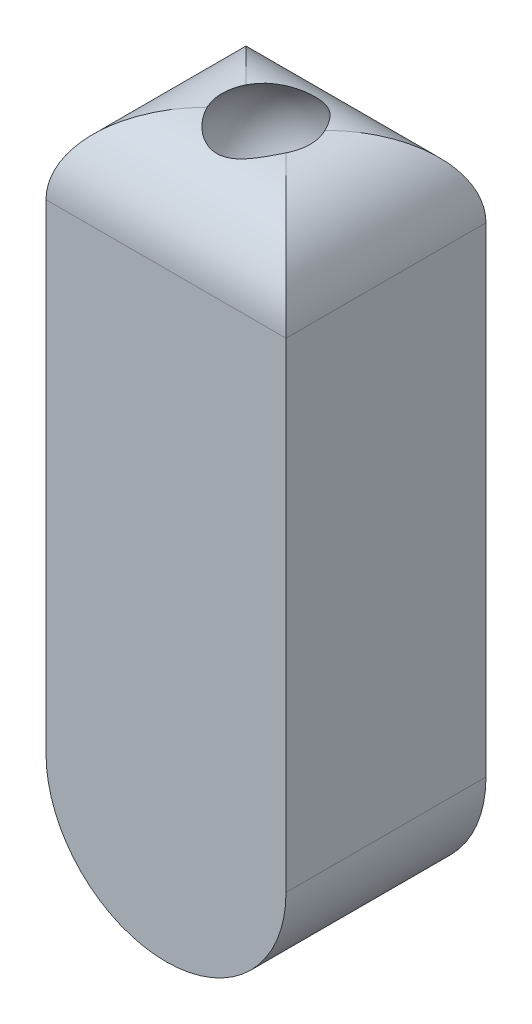
SolidWorks part; units mm, degrees
ref_plane "Front Plane" through (0, 0, 0) normal (0, 0, 1) x (1, 0, 0)
ref_plane "Top Plane" through (0, 0, 0) normal (0, 1, 0) x (1, 0, 0)
ref_plane "Right Plane" through (0, 0, 0) normal (1, 0, 0) x (0, 0, -1)
sketch "Sketch1" plane through (0, 0, 0) normal (0, 0, 1) x (1, 0, 0)
  line L1 (-38.1, 88.9) -> (38.1, 88.9)
  line L2 (-38.1, 88.9) -> (-38.1, -88.9)
  line L3 (-38.1, -88.9) -> (38.1, -88.9)
  line L4 (38.1, 88.9) -> (38.1, -88.9)
  line L5 (-38.1, 88.9) -> (38.1, -88.9) construction
  line L6 (-38.1, -88.9) -> (38.1, 88.9) construction
  point P0 (0, 0)
extrude "Boss-Extrude1" add sketch "Sketch1" along normal blind 63.5
sketch "Sketch2" plane through (0, 0, 0) normal (0, 0, 1) x (1, 0, 0)
  line L0 (-38.1, -88.9) -> (38.1, -88.9) construction
  circle A0 centre (0, -88.9) radius 38.1
extrude "Boss-Extrude2" add sketch "Sketch2" along normal through all
sketch "Sketch4" plane through (0, 0, 0) normal (0, 0, 1) x (1, 0, 0)
  circle A0 centre (0, -88.9) radius 13.97
  dimension "D1" = 27.94
extrude "Cut-Extrude1" cut sketch "Sketch4" along normal blind 48.26
fillet "Fillet2" radius 25.4 4 edges at (0, 88.9, 0) (0, 88.9, 63.5) (-38.1, 88.9, 31.75) (38.1, 88.9, 31.75)
sketch "Sketch5" plane through (0, 0, 0) normal (1, 0, 0) x (0, 0, -1)
  line L0 (-31.75, 88.9) -> (-31.75, 29.3407) construction
  line L1 (-38.1, 88.9) -> (-25.4, 88.9) construction
  line L2 (-31.75, 88.9) -> (-31.75, 74.2908) construction
  line L3 (-31.75, 53.8239) -> (-31.75, 94.4639)
  arc A0 (-31.75, 94.4639) -> (-31.75, 53.8239) centre (-31.75, 74.1439) ccw
  point P6 (-45.72, 88.9)
  point P7 (-17.78, 88.9)
  dimension "D2" = 40.64
  dimension "D1" = 27.94
revolve "Cut-Revolve4" cut sketch "Sketch5" angle 360 about L3
